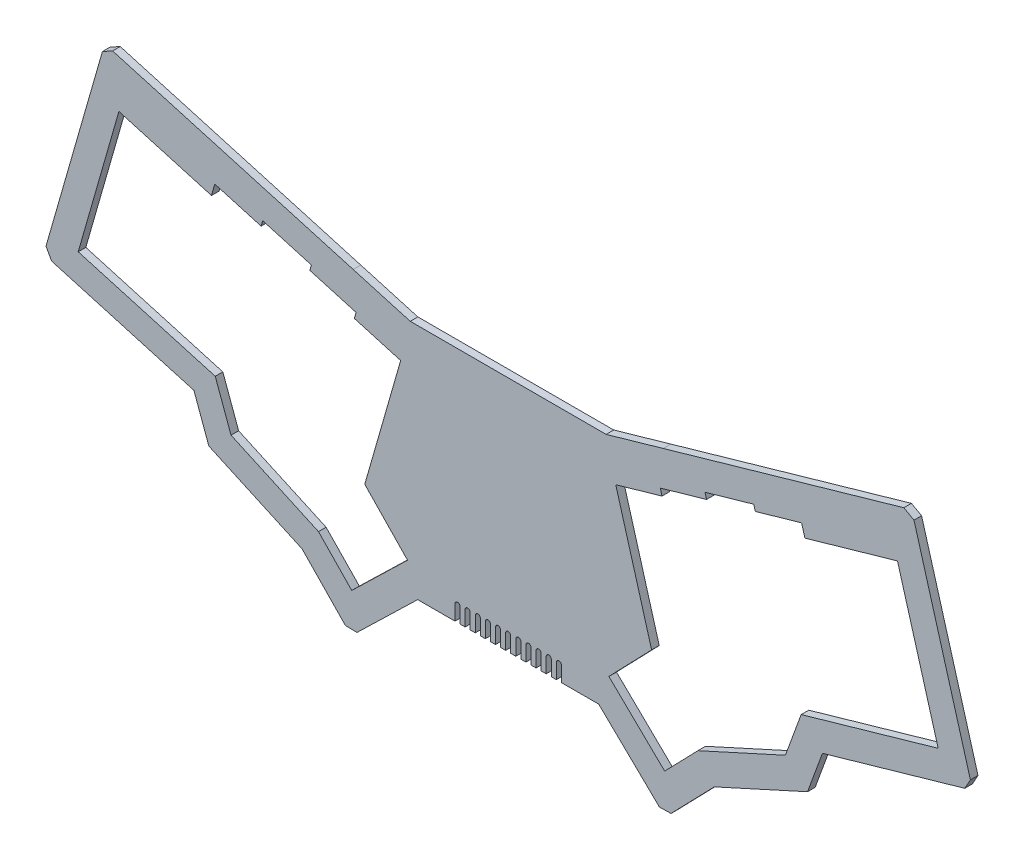
SolidWorks part; units mm, degrees
ref_plane "Plan de face" through (0, 0, 0) normal (0, 0, 1) x (1, 0, 0)
ref_plane "Plan de dessus" through (0, 0, 0) normal (0, 1, 0) x (1, 0, 0)
ref_plane "Plan de droite" through (0, 0, 0) normal (1, 0, 0) x (0, 0, -1)
sketch "Esquisse1" plane through (0, 0, 0) normal (0, 0, 1) x (1, 0, 0)
  line L0 (-121.6461, -32.0475) -> (-108.1875, -28.1884) construction
  line L1 (-108.1875, -28.1884) -> (-104.3283, -41.647) construction
  line L2 (-104.3283, -41.647) -> (-117.7869, -45.5062) construction
  line L3 (-117.7869, -45.5062) -> (-121.6461, -32.0475) construction
  line L4 (-100.1763, -37.9855) -> (-104.0355, -24.5269) construction
  line L5 (-104.0355, -24.5269) -> (-90.5769, -20.6677) construction
  line L6 (-90.5769, -20.6677) -> (-86.7177, -34.1263) construction
  line L7 (-86.7177, -34.1263) -> (-100.1763, -37.9855) construction
  line L8 (-82.5657, -30.4649) -> (-86.4249, -17.0063) construction
  line L9 (-86.4249, -17.0063) -> (-72.9663, -13.1471) construction
  line L10 (-72.9663, -13.1471) -> (-69.1071, -26.6057) construction
  line L11 (-69.1071, -26.6057) -> (-82.5657, -30.4649) construction
  line L12 (-63.6458, -27.5106) -> (-67.505, -14.0519) construction
  line L13 (-67.505, -14.0519) -> (-54.0463, -10.1927) construction
  line L14 (-54.0463, -10.1927) -> (-50.1872, -23.6514) construction
  line L15 (-50.1872, -23.6514) -> (-63.6458, -27.5106) construction
  line L16 (-44.0711, -26.8394) -> (-47.9303, -13.3808) construction
  line L17 (-47.9303, -13.3808) -> (-34.4717, -9.5216) construction
  line L18 (-34.4717, -9.5216) -> (-30.6125, -22.9802) construction
  line L19 (-30.6125, -22.9802) -> (-44.0711, -26.8394) construction
  line L20 (-25.8054, -21.6018) -> (-29.6646, -8.1432) construction
  line L21 (-29.6646, -8.1432) -> (-16.206, -4.284) construction
  line L22 (-16.206, -4.284) -> (-12.3468, -17.7426) construction
  line L23 (-12.3468, -17.7426) -> (-25.8054, -21.6018) construction
  line L24 (-116.4086, -50.3128) -> (-102.95, -46.4536) construction
  line L25 (-102.95, -46.4536) -> (-99.0908, -59.9122) construction
  line L26 (-99.0908, -59.9122) -> (-112.5494, -63.7714) construction
  line L27 (-112.5494, -63.7714) -> (-116.4086, -50.3128) construction
  line L28 (-98.798, -42.7922) -> (-85.3394, -38.933) construction
  line L29 (-85.3394, -38.933) -> (-81.4802, -52.3916) construction
  line L30 (-81.4802, -52.3916) -> (-94.9388, -56.2508) construction
  line L31 (-94.9388, -56.2508) -> (-98.798, -42.7922) construction
  line L32 (-81.1874, -35.2715) -> (-67.7288, -31.4123) construction
  line L33 (-67.7288, -31.4123) -> (-63.8696, -44.8709) construction
  line L34 (-63.8696, -44.8709) -> (-77.3282, -48.7301) construction
  line L35 (-77.3282, -48.7301) -> (-81.1874, -35.2715) construction
  line L36 (-62.2675, -32.3172) -> (-48.8089, -28.458) construction
  line L37 (-48.8089, -28.458) -> (-44.9497, -41.9166) construction
  line L38 (-44.9497, -41.9166) -> (-58.4083, -45.7758) construction
  line L39 (-58.4083, -45.7758) -> (-62.2675, -32.3172) construction
  line L40 (-42.6928, -31.646) -> (-29.2342, -27.7869) construction
  line L41 (-29.2342, -27.7869) -> (-25.375, -41.2455) construction
  line L42 (-25.375, -41.2455) -> (-38.8336, -45.1047) construction
  line L43 (-38.8336, -45.1047) -> (-42.6928, -31.646) construction
  line L44 (-24.4271, -26.4084) -> (-10.9685, -22.5492) construction
  line L45 (-10.9685, -22.5492) -> (-7.1093, -36.0078) construction
  line L46 (-7.1093, -36.0078) -> (-20.5679, -39.867) construction
  line L47 (-20.5679, -39.867) -> (-24.4271, -26.4084) construction
  line L48 (-19.1896, -44.6737) -> (-5.731, -40.8145) construction
  line L49 (-5.731, -40.8145) -> (-1.8718, -54.2731) construction
  line L50 (-1.8718, -54.2731) -> (-15.3304, -58.1323) construction
  line L51 (-15.3304, -58.1323) -> (-19.1896, -44.6737) construction
  line L52 (-37.4554, -49.9113) -> (-23.9967, -46.0521) construction
  line L53 (-23.9967, -46.0521) -> (-20.1376, -59.5107) construction
  line L54 (-20.1376, -59.5107) -> (-33.5962, -63.3699) construction
  line L55 (-33.5962, -63.3699) -> (-37.4554, -49.9113) construction
  line L56 (-57.03, -50.5825) -> (-43.5714, -46.7233) construction
  line L57 (-43.5714, -46.7233) -> (-39.7122, -60.1819) construction
  line L58 (-39.7122, -60.1819) -> (-53.1708, -64.0411) construction
  line L59 (-53.1708, -64.0411) -> (-57.03, -50.5825) construction
  line L60 (-75.9499, -53.5368) -> (-62.4913, -49.6776) construction
  line L61 (-62.4913, -49.6776) -> (-58.6321, -63.1362) construction
  line L62 (-58.6321, -63.1362) -> (-72.0908, -66.9954) construction
  line L63 (-72.0908, -66.9954) -> (-75.9499, -53.5368) construction
  line L64 (-93.5605, -61.0574) -> (-80.1019, -57.1982) construction
  line L65 (-80.1019, -57.1982) -> (-76.2427, -70.6569) construction
  line L66 (-76.2427, -70.6569) -> (-89.7013, -74.516) construction
  line L67 (-89.7013, -74.516) -> (-93.5605, -61.0574) construction
  line L68 (-111.1711, -68.5781) -> (-97.7125, -64.7189) construction
  line L69 (-97.7125, -64.7189) -> (-93.8533, -78.1775) construction
  line L70 (-93.8533, -78.1775) -> (-107.3119, -82.0367) construction
  line L71 (-107.3119, -82.0367) -> (-111.1711, -68.5781) construction
  line L72 (-79.0181, -77.3048) -> (-65.5595, -73.4456) construction
  line L73 (-65.5595, -73.4456) -> (-61.7003, -86.9042) construction
  line L74 (-61.7003, -86.9042) -> (-75.1589, -90.7634) construction
  line L75 (-75.1589, -90.7634) -> (-79.0181, -77.3048) construction
  line L76 (-99.4001, -88.1351) -> (-87.3916, -80.9362)
  line L77 (-87.3916, -80.9362) -> (-80.1927, -92.9448)
  line L78 (-80.1927, -92.9448) -> (-92.2012, -100.1436)
  line L79 (-92.2012, -100.1436) -> (-99.4001, -88.1351)
  line L80 (-120.0498, -100.4367) -> (-110.317, -90.3719)
  line L81 (-110.317, -90.3719) -> (-100.2522, -100.1047)
  line L82 (-100.2522, -100.1047) -> (-109.985, -110.1695)
  line L83 (-109.985, -110.1695) -> (-120.0498, -100.4367)
  line L86 (0.634, -55.7756) -> (-52.9527, -71.1413) construction
  line L89 (-59.2205, -88.2424) -> (-52.9527, -71.1413) construction
  line L96 (-93.4066, -103.0586) -> (-59.4637, -88.3612) construction
  line L97 (-105.418, -115.2057) -> (-93.9754, -103.3509) construction
  line L98 (-126.5332, -96.9919) -> (-107.5003, -115.385) construction
  line L99 (-167.7972, -50.1766) -> (-183.2082, -64.014) construction
  line L100 (-106.3822, -25.4572) -> (-123.6848, -30.4187) construction
  line L101 (-72.1178, -10.6906) -> (-88.4663, -15.3784) construction
  line L102 (-53.2337, -7.6163) -> (-70.5393, -12.5786) construction
  line L103 (-33.6604, -6.9452) -> (-50.9661, -11.9075) construction
  line L104 (-15.3965, -1.7081) -> (-31.745, -6.396) construction
  line L105 (0.5403, -55.2132) -> (-14.6896, -2.0999) construction
  line L106 (-16.199, -60.6113) -> (0.1495, -55.9235) construction
  line L107 (-52.7198, -71.0835) -> (-18.1144, -61.1606) construction
  line L108 (-59.1184, -88.0534) -> (-52.9674, -71.2752) construction
  line L109 (-183.2082, -64.014) -> (-173.1824, -64.9357) construction
  line L113 (-102.2678, -134.438) -> (-84.7238, -116.3191) construction
  line L114 (-84.7238, -116.3191) -> (-47.2969, -99.2981) construction
  line L115 (-47.2969, -99.2981) -> (-41.4917, -83.4594) construction
  line L116 (14.3812, -67.4381) -> (-41.4917, -83.4594) construction
  line L117 (17.8093, -61.2536) -> (-5.1371, 18.7701) construction
  line L122 (-11.3217, 22.1985) -> (-107.4545, -5.3614) construction
  line L129 (-167.7953, -27.6055) -> (-167.7953, -64.7189) construction
  line L130 (-242.0685, -103.8419) -> (-276.37, -88.2424) construction
  line L131 (-229.5108, -116.8112) -> (-242.0685, -103.8419) construction
  line L138 (-208.9328, -96.8551) -> (-229.5108, -116.8112) construction
  line L139 (-225.5107, -79.6567) -> (-208.9328, -96.8551) construction
  line L140 (-109.3352, -134.5492) -> (-102.2678, -134.438) construction
  line L142 (-5.1371, 18.7701) -> (-11.3217, 22.1985) construction
  line L143 (-211.4691, -30.6868) -> (-225.5107, -79.6567) construction
  line L147 (-114.18, -7.2899) -> (-107.4545, -5.3614) construction
  line L148 (-114.18, -7.2899) -> (-123.7936, -10.0465) construction
  line L154 (-4.3102, 15.8863) -> (-127.3606, -19.3904) construction
  line L155 (-131.531, -101.8802) -> (-105.9239, -126.7133) construction
  line L156 (-105.9239, -126.7133) -> (-89.4162, -109.6646) construction
  line L157 (-128.0696, -96.8789) -> (-106.0575, -118.2258)
  line L158 (-106.0575, -118.2258) -> (-92.9354, -104.6737)
  line L159 (-92.9354, -104.6737) -> (-58.4256, -88.9794)
  line L160 (-58.4256, -88.9794) -> (-52.1886, -71.9625)
  line L161 (1.8709, -56.4612) -> (-52.1886, -71.9625)
  line L162 (1.8709, -56.4612) -> (-14.1861, -0.4639)
  line L163 (-14.1861, -0.4639) -> (-50.7166, -10.9388)
  line L164 (-50.7166, -10.9388) -> (-52.026, -6.3725)
  line L165 (-52.026, -6.3725) -> (-70.2913, -11.61)
  line L166 (-70.2913, -11.61) -> (-70.911, -9.4488)
  line L167 (-70.911, -9.4488) -> (-90.1377, -14.9608)
  line L168 (-90.1377, -14.9608) -> (-89.5177, -17.1231)
  line L169 (-89.5177, -17.1231) -> (-107.783, -22.3606)
  line L170 (-107.783, -22.3606) -> (-107.0938, -24.7639)
  line L171 (-107.0938, -24.7639) -> (-125.3583, -30.0011)
  line L172 (-125.3583, -30.0011) -> (-111.2001, -79.378)
  line L173 (-111.2001, -79.378) -> (-127.3777, -96.1611)
  line L174 (-89.4162, -109.6646) -> (-53.6562, -93.4017) construction
  line L175 (-53.6562, -93.4017) -> (-47.6042, -76.8897) construction
  line L176 (9.2923, -60.5749) -> (-47.6042, -76.8897) construction
  line L177 (9.2923, -60.5749) -> (-12.0005, 13.6817) construction
  line L178 (-229.7336, -25.4495) -> (-211.4691, -30.6868) construction
  line L179 (-229.0444, -23.0462) -> (-229.7336, -25.4495) construction
  line L180 (-173.1824, -64.9357) -> (-167.7972, -60.1004) construction
  line L181 (-247.3097, -17.8087) -> (-229.0444, -23.0462) construction
  line L185 (17.8093, -61.2536) -> (14.3812, -67.4381) construction
  line L186 (-183.2987, -65.7677) -> (-173.2729, -66.6895) construction
  line L187 (-173.2729, -66.6895) -> (-167.8052, -74.7882) construction
  line L190 (-246.6897, -15.6465) -> (-247.3097, -17.8087) construction
  line L191 (-263.9939, -10.6857) -> (-246.6897, -15.6465) construction
  line L192 (-264.6136, -12.8469) -> (-263.9939, -10.6857) construction
  line L193 (-282.8789, -7.6094) -> (-264.6136, -12.8469) construction
  line L194 (-284.1883, -12.1757) -> (-282.8789, -7.6094) construction
  line L195 (-320.7188, -1.7008) -> (-284.1883, -12.1757) construction
  line L196 (-336.2245, -55.7756) -> (-320.7188, -1.7008) construction
  line L197 (-183.2987, -65.7677) -> (-167.8052, -88.0782) construction
  line L198 (-181.8414, -71.5322) -> (-174.8684, -81.0171) construction
  line L199 (-174.8684, -81.0171) -> (-178.3549, -83.9622) construction
  line L200 (-344.8828, -60.5749) -> (-323.5901, 13.6817) construction
  line L201 (-344.8828, -60.5749) -> (-287.9863, -76.8897) construction
  line L202 (-281.9343, -93.4017) -> (-287.9863, -76.8897) construction
  line L203 (-246.1743, -109.6646) -> (-281.9343, -93.4017) construction
  line L204 (-224.3904, -79.378) -> (-208.2128, -96.1611)
  line L205 (-210.2322, -30.0011) -> (-224.3904, -79.378)
  line L206 (-228.4967, -24.7639) -> (-210.2322, -30.0011)
  line L207 (-227.8075, -22.3606) -> (-228.4967, -24.7639)
  line L208 (-246.0728, -17.1231) -> (-227.8075, -22.3606)
  line L209 (-245.4528, -14.9608) -> (-246.0728, -17.1231)
  line L210 (-264.6796, -9.4488) -> (-245.4528, -14.9608)
  line L211 (-265.2993, -11.61) -> (-264.6796, -9.4488)
  line L212 (-283.5645, -6.3725) -> (-265.2993, -11.61)
  line L213 (-284.8739, -10.9388) -> (-283.5645, -6.3725)
  line L217 (0.634, -55.7756) -> (-14.8717, -1.7008) construction
  line L220 (-14.8717, -1.7008) -> (-51.4022, -12.1757) construction
  line L221 (-51.4022, -12.1757) -> (-52.7116, -7.6094) construction
  line L222 (-52.7116, -7.6094) -> (-70.9769, -12.8469) construction
  line L223 (-70.9769, -12.8469) -> (-71.5966, -10.6857) construction
  line L224 (-71.5966, -10.6857) -> (-88.9008, -15.6465) construction
  line L225 (-88.9008, -15.6465) -> (-88.2808, -17.8087) construction
  line L226 (-88.2808, -17.8087) -> (-106.5461, -23.0462) construction
  line L227 (-106.5461, -23.0462) -> (-105.8569, -25.4495) construction
  line L228 (-105.8569, -25.4495) -> (-124.1214, -30.6868) construction
  line L231 (-124.1214, -30.6868) -> (-110.0799, -79.6567) construction
  line L232 (-110.0799, -79.6567) -> (-126.6577, -96.8551) construction
  line L233 (-126.6577, -96.8551) -> (-106.0797, -116.8112) construction
  line L234 (-106.0797, -116.8112) -> (-93.522, -103.8419) construction
  line L235 (-93.522, -103.8419) -> (-59.2205, -88.2424) construction
  line L236 (-321.4044, -0.4639) -> (-284.8739, -10.9388)
  line L237 (-337.4614, -56.4612) -> (-321.4044, -0.4639)
  line L238 (-337.4614, -56.4612) -> (-283.4019, -71.9625)
  line L239 (-277.1649, -88.9794) -> (-283.4019, -71.9625)
  line L240 (-242.6551, -104.6737) -> (-277.1649, -88.9794)
  line L241 (-229.5331, -118.2258) -> (-242.6551, -104.6737)
  line L242 (-208.2366, -97.573) -> (-229.5331, -118.2258)
  line L243 (-229.6666, -126.7133) -> (-246.1743, -109.6646) construction
  line L244 (-204.0596, -101.8802) -> (-229.6666, -126.7133) construction
  line L245 (-331.2803, 15.8863) -> (-208.2299, -19.3904) construction
  line L246 (-178.3549, -83.9622) -> (-185.8788, -75.0552) construction
  line L247 (-185.8788, -75.0552) -> (-181.8414, -71.5322) construction
  line L248 (-176.7625, -46.6332) -> (-185.5498, -54.5291) construction
  line L249 (-185.5498, -54.5291) -> (-181.1562, -59.4188) construction
  line L250 (-181.1562, -59.4188) -> (-172.3689, -51.5229) construction
  line L251 (-276.4721, -88.0534) -> (-282.6232, -71.2752) construction
  line L252 (-282.8707, -71.0835) -> (-317.4761, -61.1606) construction
  line L253 (-319.3915, -60.6113) -> (-335.74, -55.9235) construction
  line L254 (-336.1309, -55.2132) -> (-320.9009, -2.0999) construction
  line L255 (-320.194, -1.7081) -> (-303.8455, -6.396) construction
  line L256 (-301.9301, -6.9452) -> (-284.6245, -11.9075) construction
  line L257 (-282.3568, -7.6163) -> (-265.0512, -12.5786) construction
  line L258 (-263.4727, -10.6906) -> (-247.1242, -15.3784) construction
  line L259 (-229.2083, -25.4572) -> (-211.9057, -30.4187) construction
  line L260 (-172.3689, -51.5229) -> (-176.7625, -46.6332) construction
  line L261 (-209.0573, -96.9919) -> (-228.0902, -115.385) construction
  line L262 (-230.1725, -115.2057) -> (-241.6151, -103.3509) construction
  line L263 (-242.1839, -103.0586) -> (-276.1268, -88.3612) construction
  line L264 (-276.37, -88.2424) -> (-282.6379, -71.1413) construction
  line L265 (-336.2245, -55.7756) -> (-282.6379, -71.1413) construction
  line L268 (-353.3998, -61.2536) -> (-349.9717, -67.4381) construction
  line L274 (-221.4105, -7.2899) -> (-206.0252, -11.7015) construction
  line L275 (-221.4105, -7.2899) -> (-228.136, -5.3614) construction
  line L276 (-330.4534, 18.7701) -> (-324.2688, 22.1985) construction
  line L277 (-226.2553, -134.5492) -> (-233.3227, -134.438) construction
  line L281 (-324.2688, 22.1985) -> (-228.136, -5.3614) construction
  line L282 (-353.3998, -61.2536) -> (-330.4534, 18.7701) construction
  line L283 (-349.9717, -67.4381) -> (-294.0988, -83.4594) construction
  line L284 (-288.2936, -99.2981) -> (-294.0988, -83.4594) construction
  line L285 (-250.8667, -116.3191) -> (-288.2936, -99.2981) construction
  line L286 (-233.3227, -134.438) -> (-250.8667, -116.3191) construction
  line L288 (-225.6055, -110.1695) -> (-215.5407, -100.4367) construction
  line L289 (-235.3383, -100.1047) -> (-225.6055, -110.1695) construction
  line L290 (-225.2735, -90.3719) -> (-235.3383, -100.1047) construction
  line L291 (-215.5407, -100.4367) -> (-225.2735, -90.3719) construction
  line L292 (-243.3893, -100.1436) -> (-236.1904, -88.1351) construction
  line L293 (-255.3978, -92.9448) -> (-243.3893, -100.1436) construction
  line L294 (-248.1989, -80.9362) -> (-255.3978, -92.9448) construction
  line L295 (-236.1904, -88.1351) -> (-248.1989, -80.9362) construction
  line L296 (-260.4316, -90.7634) -> (-256.5724, -77.3048) construction
  line L297 (-273.8902, -86.9042) -> (-260.4316, -90.7634) construction
  line L298 (-270.031, -73.4456) -> (-273.8902, -86.9042) construction
  line L299 (-256.5724, -77.3048) -> (-270.031, -73.4456) construction
  line L300 (-228.2786, -82.0367) -> (-224.4194, -68.5781) construction
  line L301 (-241.7372, -78.1775) -> (-228.2786, -82.0367) construction
  line L302 (-237.878, -64.7189) -> (-241.7372, -78.1775) construction
  line L303 (-224.4194, -68.5781) -> (-237.878, -64.7189) construction
  line L304 (-245.8892, -74.516) -> (-242.03, -61.0574) construction
  line L305 (-259.3478, -70.6569) -> (-245.8892, -74.516) construction
  line L306 (-255.4886, -57.1982) -> (-259.3478, -70.6569) construction
  line L307 (-242.03, -61.0574) -> (-255.4886, -57.1982) construction
  line L308 (-263.4998, -66.9954) -> (-259.6406, -53.5368) construction
  line L309 (-276.9584, -63.1362) -> (-263.4998, -66.9954) construction
  line L310 (-273.0992, -49.6776) -> (-276.9584, -63.1362) construction
  line L311 (-259.6406, -53.5368) -> (-273.0992, -49.6776) construction
  line L312 (-282.4197, -64.0411) -> (-278.5605, -50.5825) construction
  line L313 (-295.8783, -60.1819) -> (-282.4197, -64.0411) construction
  line L314 (-292.0191, -46.7233) -> (-295.8783, -60.1819) construction
  line L315 (-278.5605, -50.5825) -> (-292.0191, -46.7233) construction
  line L316 (-301.9944, -63.3699) -> (-298.1352, -49.9113) construction
  line L317 (-315.453, -59.5107) -> (-301.9944, -63.3699) construction
  line L318 (-311.5938, -46.0521) -> (-315.453, -59.5107) construction
  line L319 (-298.1352, -49.9113) -> (-311.5938, -46.0521) construction
  line L320 (-320.2601, -58.1323) -> (-316.4009, -44.6737) construction
  line L321 (-333.7187, -54.2731) -> (-320.2601, -58.1323) construction
  line L322 (-329.8595, -40.8145) -> (-333.7187, -54.2731) construction
  line L323 (-316.4009, -44.6737) -> (-329.8595, -40.8145) construction
  line L324 (-315.0226, -39.867) -> (-311.1634, -26.4084) construction
  line L325 (-328.4812, -36.0078) -> (-315.0226, -39.867) construction
  line L326 (-324.622, -22.5492) -> (-328.4812, -36.0078) construction
  line L327 (-311.1634, -26.4084) -> (-324.622, -22.5492) construction
  line L328 (-296.7569, -45.1047) -> (-292.8977, -31.646) construction
  line L329 (-310.2155, -41.2455) -> (-296.7569, -45.1047) construction
  line L330 (-306.3563, -27.7869) -> (-310.2155, -41.2455) construction
  line L331 (-292.8977, -31.646) -> (-306.3563, -27.7869) construction
  line L332 (-277.1822, -45.7758) -> (-273.323, -32.3172) construction
  line L333 (-290.6408, -41.9166) -> (-277.1822, -45.7758) construction
  line L334 (-286.7817, -28.458) -> (-290.6408, -41.9166) construction
  line L335 (-273.323, -32.3172) -> (-286.7817, -28.458) construction
  line L336 (-258.2623, -48.7301) -> (-254.4031, -35.2715) construction
  line L337 (-271.7209, -44.8709) -> (-258.2623, -48.7301) construction
  line L338 (-267.8617, -31.4123) -> (-271.7209, -44.8709) construction
  line L339 (-254.4031, -35.2715) -> (-267.8617, -31.4123) construction
  line L340 (-240.6517, -56.2508) -> (-236.7925, -42.7922) construction
  line L341 (-254.1103, -52.3916) -> (-240.6517, -56.2508) construction
  line L342 (-250.2511, -38.933) -> (-254.1103, -52.3916) construction
  line L343 (-236.7925, -42.7922) -> (-250.2511, -38.933) construction
  line L344 (-223.0411, -63.7714) -> (-219.1819, -50.3128) construction
  line L345 (-236.4997, -59.9122) -> (-223.0411, -63.7714) construction
  line L346 (-232.6405, -46.4536) -> (-236.4997, -59.9122) construction
  line L347 (-219.1819, -50.3128) -> (-232.6405, -46.4536) construction
  line L348 (-323.2438, -17.7426) -> (-309.7851, -21.6018) construction
  line L349 (-319.3846, -4.284) -> (-323.2438, -17.7426) construction
  line L350 (-305.926, -8.1432) -> (-319.3846, -4.284) construction
  line L351 (-309.7851, -21.6018) -> (-305.926, -8.1432) construction
  line L352 (-304.978, -22.9802) -> (-291.5194, -26.8394) construction
  line L353 (-301.1188, -9.5216) -> (-304.978, -22.9802) construction
  line L354 (-287.6602, -13.3808) -> (-301.1188, -9.5216) construction
  line L355 (-291.5194, -26.8394) -> (-287.6602, -13.3808) construction
  line L356 (-285.4034, -23.6514) -> (-271.9448, -27.5106) construction
  line L357 (-281.5442, -10.1927) -> (-285.4034, -23.6514) construction
  line L358 (-268.0856, -14.0519) -> (-281.5442, -10.1927) construction
  line L359 (-271.9448, -27.5106) -> (-268.0856, -14.0519) construction
  line L360 (-266.4834, -26.6057) -> (-253.0248, -30.4649) construction
  line L361 (-262.6242, -13.1471) -> (-266.4834, -26.6057) construction
  line L362 (-249.1656, -17.0063) -> (-262.6242, -13.1471) construction
  line L363 (-253.0248, -30.4649) -> (-249.1656, -17.0063) construction
  line L364 (-248.8728, -34.1263) -> (-235.4142, -37.9855) construction
  line L365 (-245.0136, -20.6677) -> (-248.8728, -34.1263) construction
  line L366 (-231.555, -24.5269) -> (-245.0136, -20.6677) construction
  line L367 (-235.4142, -37.9855) -> (-231.555, -24.5269) construction
  line L368 (-217.8036, -45.5062) -> (-213.9444, -32.0475) construction
  line L369 (-231.2622, -41.647) -> (-217.8036, -45.5062) construction
  line L370 (-227.4031, -28.1884) -> (-231.2622, -41.647) construction
  line L371 (-213.9444, -32.0475) -> (-227.4031, -28.1884) construction
  line L372 (-226.2553, -134.5492) -> (-194.0347, -103.3509) construction
  line L373 (-109.3352, -134.5492) -> (-141.5559, -103.3509) construction
  line L374 (-141.5559, -103.3509) -> (-194.0347, -103.3509) construction
  line L375 (-167.7972, -50.1766) -> (-152.3861, -64.014) construction
  line L376 (-162.4119, -64.9357) -> (-167.7972, -60.1004) construction
  line L377 (-162.3376, -66.6895) -> (-167.8052, -74.7882) construction
  line L378 (-152.3118, -65.7677) -> (-167.8052, -88.0782) construction
  line L379 (-163.2254, -51.5229) -> (-158.8318, -46.6332) construction
  line L380 (-154.4381, -59.4188) -> (-163.2254, -51.5229) construction
  line L381 (-150.0445, -54.5291) -> (-154.4381, -59.4188) construction
  line L382 (-158.8318, -46.6332) -> (-150.0445, -54.5291) construction
  line L383 (-149.7316, -75.0552) -> (-153.7691, -71.5322) construction
  line L384 (-157.2555, -83.9622) -> (-149.7316, -75.0552) construction
  line L385 (-160.742, -81.0171) -> (-157.2555, -83.9622) construction
  line L386 (-153.7691, -71.5322) -> (-160.742, -81.0171) construction
  line L387 (-152.3118, -65.7677) -> (-162.3376, -66.6895) construction
  line L388 (-152.3861, -64.014) -> (-162.4119, -64.9357) construction
  line L389 (-206.0252, -11.7015) -> (-129.5654, -11.7015) construction
  line L390 (-119.0708, -62.7964) -> (-130.6498, -22.4155) construction
  line L391 (-123.5545, -47.16) -> (-127.4136, -33.7014) construction
  line L392 (-120.442, -65.2702) -> (-138.2688, -70.3819) construction
  line L393 (-140.7426, -69.0107) -> (-154.4194, -21.3141) construction
  line L394 (-167.1758, -11.7015) -> (-206.0252, -11.7015) construction
  line L395 (-154.4194, -21.3141) -> (-167.1758, -11.7015) construction
  line L396 (-123.7936, -10.0465) -> (-130.6498, -22.4155) construction
  line L397 (-138.2688, -70.3819) -> (-140.7426, -69.0107) construction
  line L398 (-119.0708, -62.7964) -> (-120.442, -65.2702) construction
  line L399 (-129.5654, -11.7015) -> (-123.7936, -10.0465) construction
  line L400 (-165.8487, -12.7015) -> (-206.1657, -12.7015) construction
  line L401 (-221.6861, -8.2511) -> (-206.1657, -12.7015) construction
  line L402 (-221.6861, -8.2511) -> (-228.4116, -6.3226) construction
  line L403 (-324.1462, 21.1231) -> (-228.4116, -6.3226) construction
  line L404 (-329.6063, 18.0963) -> (-324.1462, 21.1231) construction
  line L405 (-352.3244, -61.1311) -> (-329.6063, 18.0963) construction
  line L406 (-352.3244, -61.1311) -> (-349.2979, -66.591) construction
  line L407 (-349.2979, -66.591) -> (-293.3347, -82.6382) construction
  line L408 (-287.4987, -98.561) -> (-293.3347, -82.6382) construction
  line L409 (-250.2802, -115.4872) -> (-287.4987, -98.561) construction
  line L410 (-232.8926, -133.4446) -> (-250.2802, -115.4872) construction
  line L411 (-226.6535, -133.5428) -> (-232.8926, -133.4446) construction
  line L412 (-226.6535, -133.5428) -> (-194.4395, -102.3509) construction
  line L413 (-141.1511, -102.3509) -> (-194.4395, -102.3509) construction
  line L414 (-108.937, -133.5428) -> (-141.1511, -102.3509) construction
  line L415 (-108.937, -133.5428) -> (-102.6979, -133.4446) construction
  line L416 (-102.6979, -133.4446) -> (-85.3104, -115.4872) construction
  line L417 (-85.3104, -115.4872) -> (-48.0918, -98.561) construction
  line L418 (-48.0918, -98.561) -> (-42.2558, -82.6382) construction
  line L419 (13.7074, -66.591) -> (-42.2558, -82.6382) construction
  line L420 (16.7339, -61.1311) -> (13.7074, -66.591) construction
  line L421 (16.7339, -61.1311) -> (-5.9842, 18.0963) construction
  line L422 (-5.9842, 18.0963) -> (-11.4443, 21.1231) construction
  line L423 (-11.4443, 21.1231) -> (-107.1789, -6.3226) construction
  line L424 (-113.9044, -8.2511) -> (-107.1789, -6.3226) construction
  line L425 (-113.9044, -8.2511) -> (-124.4792, -11.2834) construction
  line L426 (-167.1758, -12.7015) -> (-206.1657, -12.7015) construction
  line L427 (-113.9044, -8.2511) -> (-123.5179, -11.0078) construction
  line L428 (-165.8487, -12.7015) -> (-154.4194, -21.3141) construction
  line L429 (-130.6498, -22.4155) -> (-124.4792, -11.2834) construction
  line L430 (-208.2366, -97.573) -> (-207.4919, -96.8551)
  line L431 (-207.4919, -96.8551) -> (-208.2128, -96.1611)
  line L432 (-127.3777, -96.1611) -> (-128.0696, -96.8789)
  line L433 (-221.9618, -9.2124) -> (-206.3062, -13.7015) construction
  line L434 (-166.1833, -13.7015) -> (-206.3062, -13.7015) construction
  line L435 (-166.1833, -13.7015) -> (-155.2884, -21.9114) construction
  line L436 (-141.5897, -69.6845) -> (-155.2884, -21.9114) construction
  line L437 (-138.3914, -71.4574) -> (-141.5897, -69.6845) construction
  line L438 (-119.7682, -66.1172) -> (-138.3914, -71.4574) construction
  line L439 (-117.9954, -62.9189) -> (-119.7682, -66.1172) construction
  line L440 (-117.9954, -62.9189) -> (-129.5744, -22.538) construction
  line L441 (-129.5744, -22.538) -> (-123.8054, -12.1305) construction
  line L442 (-113.6287, -9.2124) -> (-123.8054, -12.1305) construction
  line L443 (-113.6287, -9.2124) -> (-106.9033, -7.2839) construction
  line L444 (-11.5669, 20.0477) -> (-106.9033, -7.2839) construction
  line L445 (-6.8313, 17.4225) -> (-11.5669, 20.0477) construction
  line L446 (15.6584, -61.0086) -> (-6.8313, 17.4225) construction
  line L447 (15.6584, -61.0086) -> (13.0336, -65.7439) construction
  line L448 (13.0336, -65.7439) -> (-43.0198, -81.817) construction
  line L449 (-48.8867, -97.824) -> (-43.0198, -81.817) construction
  line L450 (-85.8969, -114.6554) -> (-48.8867, -97.824) construction
  line L451 (-103.128, -132.4513) -> (-85.8969, -114.6554) construction
  line L452 (-108.5388, -132.5364) -> (-103.128, -132.4513) construction
  line L453 (-108.5388, -132.5364) -> (-140.7463, -101.3509) construction
  line L454 (-140.7463, -101.3509) -> (-194.8443, -101.3509) construction
  line L455 (-227.0517, -132.5364) -> (-194.8443, -101.3509) construction
  line L456 (-227.0517, -132.5364) -> (-232.4625, -132.4513) construction
  line L457 (-232.4625, -132.4513) -> (-249.6936, -114.6554) construction
  line L458 (-249.6936, -114.6554) -> (-286.7038, -97.824) construction
  line L459 (-286.7038, -97.824) -> (-292.5707, -81.817) construction
  line L460 (-348.6241, -65.7439) -> (-292.5707, -81.817) construction
  line L461 (-351.2489, -61.0086) -> (-348.6241, -65.7439) construction
  line L462 (-351.2489, -61.0086) -> (-328.7592, 17.4225) construction
  line L463 (-328.7592, 17.4225) -> (-324.0237, 20.0477) construction
  line L464 (-324.0237, 20.0477) -> (-228.6872, -7.2839) construction
  line L465 (-221.9618, -9.2124) -> (-228.6872, -7.2839) construction
  line L466 (-129.1437, -14.7015) -> (-206.4468, -14.7015)
  line L467 (-222.2374, -10.1736) -> (-206.4468, -14.7015)
  line L468 (-222.2374, -10.1736) -> (-228.9628, -8.2452)
  line L469 (-323.9011, 18.9722) -> (-228.9628, -8.2452)
  line L470 (-327.9121, 16.7487) -> (-323.9011, 18.9722)
  line L471 (-350.1735, -60.886) -> (-327.9121, 16.7487)
  line L472 (-350.1735, -60.886) -> (-347.9503, -64.8968)
  line L473 (-347.9503, -64.8968) -> (-291.8066, -80.9958)
  line L474 (-285.9089, -97.0869) -> (-291.8066, -80.9958)
  line L475 (-249.1071, -113.8236) -> (-285.9089, -97.0869)
  line L476 (-232.0324, -131.4579) -> (-249.1071, -113.8236)
  line L477 (-227.4499, -131.53) -> (-232.0324, -131.4579)
  line L478 (-227.4499, -131.53) -> (-203.5112, -108.3509)
  line L479 (-140.3415, -100.3509) -> (-195.2491, -100.3509) construction
  line L480 (-108.1406, -131.53) -> (-132.0793, -108.3509)
  line L481 (-108.1406, -131.53) -> (-103.5582, -131.4579)
  line L482 (-103.5582, -131.4579) -> (-86.4835, -113.8236)
  line L483 (-86.4835, -113.8236) -> (-49.6816, -97.0869)
  line L484 (-49.6816, -97.0869) -> (-43.7839, -80.9958)
  line L485 (12.3598, -64.8968) -> (-43.7839, -80.9958)
  line L486 (14.583, -60.886) -> (12.3598, -64.8968)
  line L487 (14.583, -60.886) -> (-7.6784, 16.7487)
  line L488 (-7.6784, 16.7487) -> (-11.6894, 18.9722)
  line L489 (-11.6894, 18.9722) -> (-106.6277, -8.2452)
  line L490 (-113.3531, -10.1736) -> (-106.6277, -8.2452)
  line L491 (-113.3531, -10.1736) -> (-129.1437, -14.7015)
  line L492 (-128.499, -22.6605) -> (-123.1316, -12.9776) construction
  line L493 (-116.9199, -63.0414) -> (-128.499, -22.6605) construction
  line L494 (-116.9199, -63.0414) -> (-119.0944, -66.9643) construction
  line L495 (-119.0944, -66.9643) -> (-138.5139, -72.5328) construction
  line L496 (-138.5139, -72.5328) -> (-142.4368, -70.3583) construction
  line L497 (-142.4368, -70.3583) -> (-156.1575, -22.5087) construction
  line L498 (-166.5179, -14.7015) -> (-156.1575, -22.5087) construction
  line L499 (-166.5179, -14.7015) -> (-206.4468, -14.7015) construction
  line L500 (-113.3531, -10.1736) -> (-123.1316, -12.9776) construction
  line L501 (-132.0793, -108.3509) -> (-203.5112, -108.3509)
  line L502 (-140.3415, -108.3509) -> (-195.2491, -108.3509) construction
  line L504 (-227.4499, -131.53) -> (-195.2491, -100.3509) construction
  line L505 (-108.1406, -131.53) -> (-140.3415, -100.3509) construction
  circle A2 centre (-12.0005, 13.6817) radius 1.6 construction
  circle A3 centre (-12.0005, 13.6817) radius 3 construction
  circle A4 centre (-118.7579, -16.9241) radius 3 construction
  circle A5 centre (9.2923, -60.5749) radius 3 construction
  circle A6 centre (-53.6562, -93.4017) radius 3 construction
  circle A7 centre (-105.9239, -126.7133) radius 3 construction
  circle A8 centre (-131.531, -101.8802) radius 3 construction
  circle A10 centre (-147.4897, -45.973) radius 1.6 construction
  circle A11 centre (-323.5901, 13.6817) radius 3 construction
  circle A12 centre (-188.1008, -45.973) radius 1.6 construction
  circle A14 centre (-204.0596, -101.8802) radius 3 construction
  circle A15 centre (-229.6666, -126.7133) radius 3 construction
  circle A16 centre (-281.9343, -93.4017) radius 3 construction
  circle A17 centre (-344.8828, -60.5749) radius 3 construction
  circle A18 centre (-216.8326, -16.9241) radius 3 construction
  circle A19 centre (-323.5901, 13.6817) radius 1.6 construction
  circle A20 centre (-167.7953, -27.6055) radius 3 construction
  point P138 (-167.7953, -27.6055)
  point P139 (-6.5153, 23.5764)
  point P150 (-169.1046, -23.0392)
  point P200 (19.1875, -66.0599)
  point P203 (-141.5228, -71.3355)
  point P204 (-141.5228, 1.5705)
  point P263 (-133.4062, -12.8029)
  point P264 (-118.5195, -64.7189)
  point P283 (-140.1914, -70.9332)
  point P284 (-157.1758, -11.7015)
  point P405 (-354.778, -66.0599)
  point P406 (-329.0752, 23.5764)
  dimension "D3" = 3.2
  dimension "D4" = 6
  dimension "D6" = 6
  dimension "D7" = 6
  dimension "D8" = 6
  dimension "D9" = 6
  dimension "D10" = 6
  dimension "D16" = 3.2
  dimension "D14" = 6
  dimension "D2" = 6
  dimension "D5" = 1
  dimension "D11" = 1
  dimension "D18" = 1
  dimension "D20" = 8
extrude "Boss.-Extru.1" add sketch "Esquisse1" along normal blind 3 contours L490 L491 L466 L467 L468 L469 L470 L471 L472 L473 L474 L475 L476 L477 L478 L479 L480 L481 L482 L483 L484 L485 L486 L487 L488 L489 L431 L430 L242 L241 L240 L239 L238 L237 L236 L213 L212 L211 L210 L209 L208 L207 L206 L205 L204 L432 L173 L172 L171
sketch "Esquisse2" plane through (0, 0, 3) normal (0, 0, 1) x (1, 0, 0)
  line L0 (-167.7953, -108.3509) -> (-167.7953, -102.3509) construction
  line L1 (-132.0793, -108.3509) -> (-203.5112, -108.3509) construction
  line L2 (-168.7953, -108.3509) -> (-168.7953, -102.3509)
  line L3 (-166.7953, -108.3509) -> (-166.7953, -102.3509)
  line L4 (-163.7953, -108.3509) -> (-163.7953, -102.3509) construction
  line L5 (-164.7953, -108.3509) -> (-164.7953, -102.3509)
  line L6 (-162.7953, -108.3509) -> (-162.7953, -102.3509)
  line L7 (-159.7953, -108.3509) -> (-159.7953, -102.3509) construction
  line L8 (-160.7953, -108.3509) -> (-160.7953, -102.3509)
  line L9 (-158.7953, -108.3509) -> (-158.7953, -102.3509)
  line L10 (-155.7953, -108.3509) -> (-155.7953, -102.3509) construction
  line L11 (-156.7953, -108.3509) -> (-156.7953, -102.3509)
  line L12 (-154.7953, -108.3509) -> (-154.7953, -102.3509)
  line L13 (-151.7953, -108.3509) -> (-151.7953, -102.3509) construction
  line L14 (-152.7953, -108.3509) -> (-152.7953, -102.3509)
  line L15 (-150.7953, -108.3509) -> (-150.7953, -102.3509)
  line L16 (-147.7953, -108.3509) -> (-147.7953, -102.3509) construction
  line L17 (-148.7953, -108.3509) -> (-148.7953, -102.3509)
  line L18 (-146.7953, -108.3509) -> (-146.7953, -102.3509)
  line L19 (-171.7953, -108.3509) -> (-171.7953, -102.3509) construction
  line L20 (-172.7953, -108.3509) -> (-172.7953, -102.3509)
  line L21 (-170.7953, -108.3509) -> (-170.7953, -102.3509)
  line L22 (-175.7953, -108.3509) -> (-175.7953, -102.3509) construction
  line L23 (-176.7953, -108.3509) -> (-176.7953, -102.3509)
  line L24 (-174.7953, -108.3509) -> (-174.7953, -102.3509)
  line L25 (-179.7953, -108.3509) -> (-179.7953, -102.3509) construction
  line L26 (-180.7953, -108.3509) -> (-180.7953, -102.3509)
  line L27 (-178.7953, -108.3509) -> (-178.7953, -102.3509)
  line L28 (-183.7953, -108.3509) -> (-183.7953, -102.3509) construction
  line L29 (-184.7953, -108.3509) -> (-184.7953, -102.3509)
  line L30 (-182.7953, -108.3509) -> (-182.7953, -102.3509)
  line L31 (-187.7953, -108.3509) -> (-187.7953, -102.3509) construction
  line L32 (-188.7953, -108.3509) -> (-188.7953, -102.3509)
  line L33 (-186.7953, -108.3509) -> (-186.7953, -102.3509)
  arc A0 (-168.7953, -108.3509) -> (-166.7953, -108.3509) centre (-167.7953, -108.3509) ccw
  arc A1 (-166.7953, -102.3509) -> (-168.7953, -102.3509) centre (-167.7953, -102.3509) ccw
  arc A2 (-164.7953, -108.3509) -> (-162.7953, -108.3509) centre (-163.7953, -108.3509) ccw
  arc A3 (-162.7953, -102.3509) -> (-164.7953, -102.3509) centre (-163.7953, -102.3509) ccw
  arc A4 (-160.7953, -108.3509) -> (-158.7953, -108.3509) centre (-159.7953, -108.3509) ccw
  arc A5 (-158.7953, -102.3509) -> (-160.7953, -102.3509) centre (-159.7953, -102.3509) ccw
  arc A6 (-156.7953, -108.3509) -> (-154.7953, -108.3509) centre (-155.7953, -108.3509) ccw
  arc A7 (-154.7953, -102.3509) -> (-156.7953, -102.3509) centre (-155.7953, -102.3509) ccw
  arc A8 (-152.7953, -108.3509) -> (-150.7953, -108.3509) centre (-151.7953, -108.3509) ccw
  arc A9 (-150.7953, -102.3509) -> (-152.7953, -102.3509) centre (-151.7953, -102.3509) ccw
  arc A10 (-148.7953, -108.3509) -> (-146.7953, -108.3509) centre (-147.7953, -108.3509) ccw
  arc A11 (-146.7953, -102.3509) -> (-148.7953, -102.3509) centre (-147.7953, -102.3509) ccw
  arc A12 (-172.7953, -108.3509) -> (-170.7953, -108.3509) centre (-171.7953, -108.3509) ccw
  arc A13 (-170.7953, -102.3509) -> (-172.7953, -102.3509) centre (-171.7953, -102.3509) ccw
  arc A14 (-176.7953, -108.3509) -> (-174.7953, -108.3509) centre (-175.7953, -108.3509) ccw
  arc A15 (-174.7953, -102.3509) -> (-176.7953, -102.3509) centre (-175.7953, -102.3509) ccw
  arc A16 (-180.7953, -108.3509) -> (-178.7953, -108.3509) centre (-179.7953, -108.3509) ccw
  arc A17 (-178.7953, -102.3509) -> (-180.7953, -102.3509) centre (-179.7953, -102.3509) ccw
  arc A18 (-184.7953, -108.3509) -> (-182.7953, -108.3509) centre (-183.7953, -108.3509) ccw
  arc A19 (-182.7953, -102.3509) -> (-184.7953, -102.3509) centre (-183.7953, -102.3509) ccw
  arc A20 (-188.7953, -108.3509) -> (-186.7953, -108.3509) centre (-187.7953, -108.3509) ccw
  arc A21 (-186.7953, -102.3509) -> (-188.7953, -102.3509) centre (-187.7953, -102.3509) ccw
  point P4 (-167.7953, -105.3509)
  point P12 (-163.7953, -105.3509)
  point P19 (-159.7953, -105.3509)
  point P26 (-155.7953, -105.3509)
  point P33 (-151.7953, -105.3509)
  point P40 (-147.7953, -105.3509)
  point P47 (-171.7953, -105.3509)
  point P54 (-175.7953, -105.3509)
  point P61 (-179.7953, -105.3509)
  point P68 (-183.7953, -105.3509)
  point P75 (-187.7953, -105.3509)
  dimension "D1" = 6
  dimension "D2" = 6
extrude "Enlèv. mat.-Extru.1" cut sketch "Esquisse2" against normal blind 10
